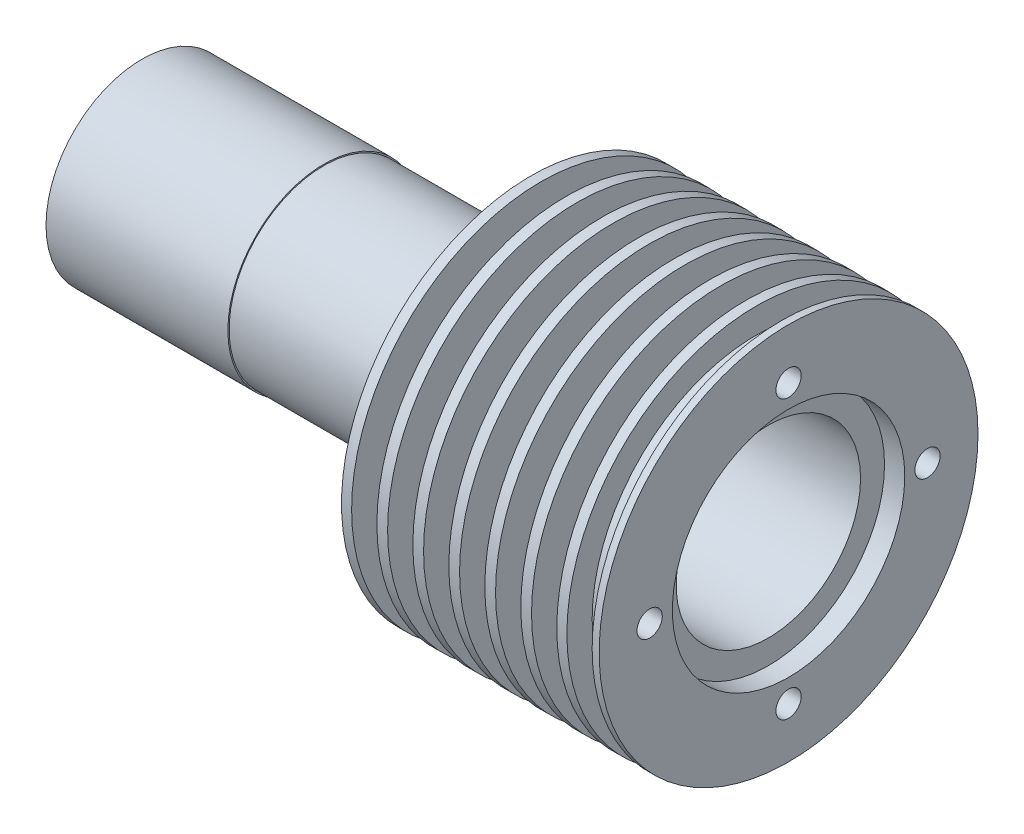
SolidWorks part; units mm, degrees
ref_plane "Front Plane" through (0, 0, 0) normal (0, 0, 1) x (1, 0, 0)
ref_plane "Top Plane" through (0, 0, 0) normal (0, 1, 0) x (1, 0, 0)
ref_plane "Right Plane" through (0, 0, 0) normal (1, 0, 0) x (0, 0, -1)
sketch "Sketch1" plane through (0, 0, 0) normal (1, 0, 0) x (0, 0, -1)
  circle A0 centre (0, 0) radius 19
  dimension "D1" = 38
extrude "Boss-Extrude1" add sketch "Sketch1" along normal blind 36
sketch "Sketch2" plane through (36, 0, 0) normal (1, 0, 0) x (0, 0, -1)
  circle A0 centre (0, 0) radius 18.75
  dimension "D1" = 37.5
extrude "Boss-Extrude2" add sketch "Sketch2" along normal blind 36
sketch "Sketch3" plane through (72, 0, 0) normal (1, 0, 0) x (0, 0, -1)
  circle A0 centre (0, 0) radius 19
  dimension "D1" = 38
extrude "Boss-Extrude3" add sketch "Sketch3" along normal blind 56
sketch "Sketch4" plane through (128, 0, 0) normal (1, 0, 0) x (0, 0, -1)
  circle A0 centre (0, 0) radius 37.5
  dimension "D1" = 75
extrude "Boss-Extrude4" add sketch "Sketch4" against normal blind 51
sketch "Sketch5" plane through (128, 0, 0) normal (1, 0, 0) x (0, 0, -1)
  circle A0 centre (0, 0) radius 18.25
  dimension "D1" = 36.5
extrude "Cut-Extrude1" cut sketch "Sketch5" against normal through all
sketch "Sketch6" plane through (0, 0, 0) normal (0, 0, 1) x (1, 0, 0)
  line L0 (128, 37.5) -> (77, 37.5) construction
  line L1 (79, 37.5) -> (84, 37.5)
  line L2 (79, 37.5) -> (79, 19)
  line L3 (79, 19) -> (84, 19)
  line L4 (84, 37.5) -> (84, 19)
  line L5 (77, 37.5) -> (77, -37.5) construction
  line L6 (86.123, 37.5) -> (91.123, 37.5)
  line L7 (91.123, 37.5) -> (91.123, 19)
  line L8 (86.123, 19) -> (91.123, 19)
  line L9 (86.123, 37.5) -> (86.123, 19)
  line L10 (93.246, 37.5) -> (98.246, 37.5)
  line L11 (98.246, 37.5) -> (98.246, 19)
  line L12 (93.246, 19) -> (98.246, 19)
  line L13 (93.246, 37.5) -> (93.246, 19)
  line L14 (100.369, 37.5) -> (105.369, 37.5)
  line L15 (105.369, 37.5) -> (105.369, 19)
  line L16 (100.369, 19) -> (105.369, 19)
  line L17 (100.369, 37.5) -> (100.369, 19)
  line L18 (107.492, 37.5) -> (112.492, 37.5)
  line L19 (112.492, 37.5) -> (112.492, 19)
  line L20 (107.492, 19) -> (112.492, 19)
  line L21 (107.492, 37.5) -> (107.492, 19)
  line L22 (114.615, 37.5) -> (119.615, 37.5)
  line L23 (119.615, 37.5) -> (119.615, 19)
  line L24 (114.615, 19) -> (119.615, 19)
  line L25 (114.615, 37.5) -> (114.615, 19)
  line L26 (0, 0) -> (128, 0) construction
  line L27 (121.615, 37.5) -> (126.615, 37.5)
  line L28 (121.615, 37.5) -> (121.615, 32.5)
  line L29 (121.615, 32.5) -> (126.615, 32.5)
  line L30 (126.615, 37.5) -> (126.615, 32.5)
  line L31 (128, -37.5) -> (128, 37.5) construction
  dimension "D1" = 5
  dimension "D2" = 2
  dimension "D3" = 18.5
  dimension "D5" = 5
  dimension "D6" = 2
  dimension "D7" = 5
  dimension "D4" = 6
revolve "Cut-Revolve1" cut sketch "Sketch6" angle 360 about L26
sketch "Sketch7" plane through (128, 0, 0) normal (1, 0, 0) x (0, 0, -1)
  circle A0 centre (0, 0) radius 27.5 construction
  circle A1 centre (0, 27.5) radius 2.5
  circle A2 centre (0, 0) radius 27.5 construction
  circle A3 centre (27.5, 0) radius 2.5
  circle A4 centre (0, 0) radius 27.5 construction
  circle A5 centre (0, -27.5) radius 2.5
  circle A6 centre (0, 0) radius 27.5 construction
  circle A7 centre (-27.5, 0) radius 2.5
  point P17 (0, 0)
  dimension "D1" = 55
  dimension "D2" = 5
  dimension "D3" = 4
extrude "Cut-Extrude2" cut sketch "Sketch7" against normal blind 9
sketch "Sketch8" plane through (128, 0, 0) normal (1, 0, 0) x (0, 0, -1)
  circle A0 centre (0, 0) radius 23
  dimension "D1" = 46
extrude "Cut-Extrude3" cut sketch "Sketch8" against normal blind 4
